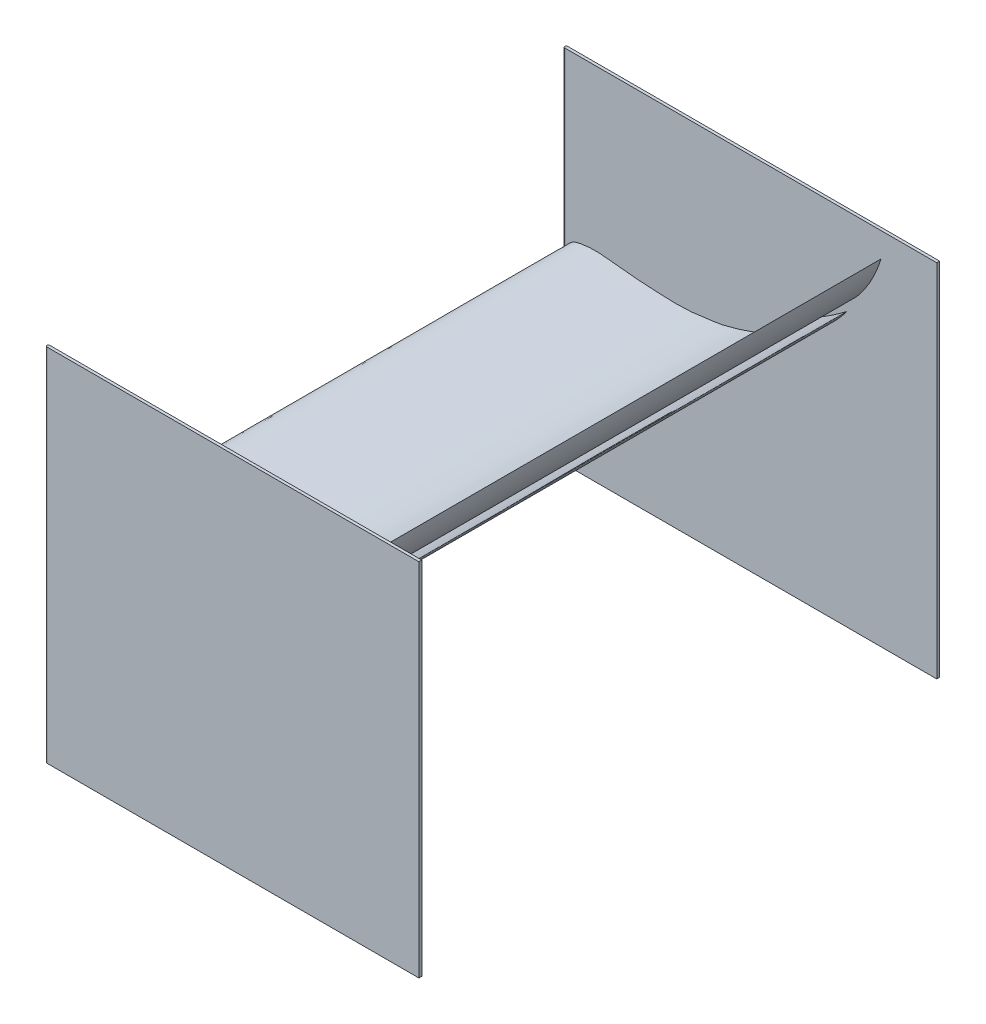
SolidWorks part; units mm, degrees
ref_plane "Front Plane" through (0, 0, 0) normal (0, 0, 1) x (1, 0, 0)
ref_plane "Top Plane" through (0, 0, 0) normal (0, 1, 0) x (1, 0, 0)
ref_plane "Right Plane" through (0, 0, 0) normal (1, 0, 0) x (0, 0, -1)
sketch "Sketch1" plane through (0, 0, 0) normal (0, 0, 1) x (1, 0, 0)
  line L0 (46.9575, 64.3181) -> (1074.8558, 208.7798) construction
sketch "Sketch2" plane through (0, 0, 0) normal (0, 0, 1) x (1, 0, 0)
  line L0 (0, 0) -> (400, 0) construction
  line L1 (0, 0) -> (399.6225, 66.8739) construction
  line L2 (0, 66.8739) -> (0, -66.8739) construction
  line L3 (10.0115, 66.8739) -> (10.0115, -116.1581) construction
  line L4 (20.0229, 66.8739) -> (20.0229, -116.1581) construction
  line L5 (30.0344, 66.8739) -> (30.0344, -116.1581) construction
  line L6 (40.0459, 66.8739) -> (40.0459, -116.1581) construction
  line L7 (50.0573, 66.8739) -> (50.0573, -116.1581) construction
  line L8 (60.0688, 66.8739) -> (60.0688, -116.1581) construction
  line L9 (70.0803, 66.8739) -> (70.0803, -116.1581) construction
  line L10 (80.0918, 66.8739) -> (80.0918, -116.1581) construction
  line L11 (90.1032, 66.8739) -> (90.1032, -116.1581) construction
  line L12 (100.1147, 66.8739) -> (100.1147, -116.1581) construction
  line L13 (110.1262, 66.8739) -> (110.1262, -116.1581) construction
  line L14 (120.1376, 66.8739) -> (120.1376, -116.1581) construction
  line L15 (130.1491, 66.8739) -> (130.1491, -116.1581) construction
  line L16 (140.1606, 66.8739) -> (140.1606, -116.1581) construction
  line L17 (150.172, 66.8739) -> (150.172, -116.1581) construction
  line L18 (160.1835, 66.8739) -> (160.1835, -116.1581) construction
  line L19 (170.195, 66.8739) -> (170.195, -116.1581) construction
  line L20 (180.2064, 66.8739) -> (180.2064, -116.1581) construction
  line L21 (190.2179, 66.8739) -> (190.2179, -116.1581) construction
  line L22 (200.2294, 66.8739) -> (200.2294, -116.1581) construction
  line L23 (210.2408, 66.8739) -> (210.2408, -116.1581) construction
  line L24 (220.2523, 66.8739) -> (220.2523, -116.1581) construction
  line L25 (230.2638, 66.8739) -> (230.2638, -116.1581) construction
  line L26 (240.2753, 66.8739) -> (240.2753, -116.1581) construction
  line L27 (250.2867, 66.8739) -> (250.2867, -116.1581) construction
  line L28 (260.2982, 66.8739) -> (260.2982, -116.1581) construction
  line L29 (270.3097, 66.8739) -> (270.3097, -116.1581) construction
  line L30 (280.3211, 66.8739) -> (280.3211, -116.1581) construction
  line L31 (290.3326, 66.8739) -> (290.3326, -116.1581) construction
  line L32 (300.3441, 66.8739) -> (300.3441, -116.1581) construction
  line L33 (310.3555, 66.8739) -> (310.3555, -116.1581) construction
  line L34 (320.367, 66.8739) -> (320.367, -116.1581) construction
  line L35 (330.3785, 66.8739) -> (330.3785, -116.1581) construction
  line L36 (340.3899, 66.8739) -> (340.3899, -116.1581) construction
  line L37 (350.4014, 66.8739) -> (350.4014, -116.1581) construction
  line L38 (360.4129, 66.8739) -> (360.4129, -116.1581) construction
  line L39 (370.4243, 66.8739) -> (370.4243, -116.1581) construction
  line L40 (380.4358, 66.8739) -> (380.4358, -116.1581) construction
  line L41 (390.4473, 66.8739) -> (390.4473, -116.1581) construction
  line L42 (400.4588, 66.8739) -> (400.4588, -116.1581) construction
  line L43 (836.1007, 66.8739) -> (-36.8556, 66.8739) construction
  line L44 (389.6225, 76.8739) -> (409.6225, 76.8739) construction
  line L45 (399.6225, 90.7703) -> (399.6225, 62.9774) construction
  line L46 (548.1427, 255.362) -> (478.7399, 156.2446) construction
  line L47 (488.7399, 146.2766) -> (482.6971, 142.1346) construction
  line L48 (389.6225, 76.8739) -> (488.7399, 146.2766) construction
  line L51 (488.7399, 194.8045) -> (488.7399, 123.7678) construction
  line L52 (478.7399, 201.6203) -> (478.7399, 116.9521) construction
  line L53 (478.7399, 156.2446) -> (614.5057, 156.2446) construction
  line L54 (389.6225, 83.3039) -> (389.6225, -27.4023) construction
  line L55 (478.7399, 146.2446) -> (614.5057, 146.2446) construction
  spline S0 degree 3 poles (8.4176, 12.2629) (-5.1, -0.6947) (8.0175, -15.4806) (19.5512, -21.724) (30.0167, -25.3022) (39.86, -28.8642) (50.0404, -30.6629) (60.0706, -32.2577) (70.0139, -34.2177) (80.101, -34.56) (90.0931, -35.3652) (100.112, -35.9529) (110.1282, -35.5072) (120.1532, -35.21) (130.1503, -34.2298) (140.19, -33.4102) (150.1782, -31.9134) (160.1704, -30.3713) (170.2408, -29.1636) (180.2083, -27.151) (190.2638, -25.3061) (200.2392, -22.8725) (210.2446, -20.4291) (220.2329, -17.8951) (230.3811, -15.7054) (240.3519, -12.3911) (253.5512, -7.3696) (266.9476, -2.8065) (280.4369, 1.6366) (290.3614, 5.8195) (300.4407, 10.0322) (310.3048, 14.8841) (323.8214, 20.8842) (337.3023, 27.2498) (350.2747, 34.8502) (364.0374, 41.2007) (378.0734, 50.4319) (389.2687, 56.9917) (404.9331, 70.6704) (388.8931, 60.8973) (380.9617, 56.8333) (370.3166, 52.1732) (360.4136, 47.7491) (350.4697, 43.0754) (340.4967, 38.8332) (330.4052, 35.261) (320.3498, 31.8494) (310.3583, 28.3259) (300.4869, 24.6622) (290.3218, 22.3006) (280.2904, 19.7619) (270.4267, 16.765) (260.336, 15.0613) (250.2769, 13.9588) (240.2662, 12.5783) (230.2787, 11.0679) (220.2867, 9.6964) (210.2433, 9.2404) (200.2287, 9.0345) (190.217, 8.2792) (180.2125, 9.1624) (170.1842, 8.7285) (160.1865, 9.5822) (150.1678, 9.9892) (140.1635, 10.7007) (130.146, 11.2145) (120.1214, 11.8409) (110.1328, 12.9697) (100.1148, 13.8501) (90.0938, 14.7159) (80.0796, 15.8427) (56.9177, 18.8475) (32.3828, 18.9634) (8.4176, 12.2629) (-5.1, -0.6947) (8.0175, -15.4806) knots -0.089629 -0.030705 -0.018228 0 0.022024 0.035622 0.048197 0.060585 0.072602 0.084545 0.096479 0.108284 0.12009 0.131879 0.143661 0.155449 0.167269 0.1791 0.190991 0.202897 0.214788 0.226766 0.238768 0.250864 0.262992 0.27512 0.287235 0.299601 0.31215 0.337082 0.349542 0.362249 0.375072 0.388091 0.40103 0.427261 0.440709 0.453892 0.481344 0.495528 0.510184 0.522428 0.535733 0.548643 0.561554 0.574511 0.587287 0.599816 0.612271 0.624763 0.637218 0.649381 0.661544 0.67375 0.685718 0.697586 0.709472 0.721375 0.733243 0.74504 0.756824 0.768611 0.780398 0.792175 0.803972 0.815766 0.827567 0.839363 0.851169 0.863006 0.874833 0.88666 0.89851 0.910371 0.969295 0.981772 1 1.022024 1.035622 1.048197 only from (0, 0) to (0, 0)
  spline S1 degree 3 poles (488.4807, 145.9571) (488.8121, 146.3498) (488.4243, 146.015) (488.0622, 145.7851) (487.2625, 145.1263) (486.2197, 144.3713) (484.8735, 143.3367) (483.2507, 142.1161) (481.3449, 140.7026) (479.1839, 139.1083) (476.7613, 137.3643) (474.1237, 135.4494) (471.2368, 133.4393) (468.1657, 131.2913) (464.8962, 129.0676) (461.4575, 126.7695) (457.874, 124.4106) (454.1513, 122.027) (450.3296, 119.6083) (446.4184, 117.1921) (442.4423, 114.7926) (438.4319, 112.4153) (434.4211, 110.0589) (430.4193, 107.7484) (426.4691, 105.4752) (422.5724, 103.27) (418.7829, 101.1054) (415.1038, 99.0189) (411.5811, 96.98) (408.2231, 95.0247) (405.0701, 93.1172) (402.1178, 91.3128) (399.4157, 89.5543) (396.9653, 87.8935) (394.7924, 86.3186) (392.9158, 84.83) (391.3498, 83.4309) (390.0835, 82.1509) (389.1526, 80.9646) (388.5665, 79.872) (388.3105, 78.8689) (388.4525, 77.9475) (389.0134, 77.2045) (389.9156, 76.685) (391.1282, 76.3842) (392.6501, 76.2546) (394.4851, 76.3138) (396.6232, 76.5794) (399.0459, 77.0357) (401.7358, 77.7205) (404.6757, 78.5968) (407.8392, 79.7049) (411.2008, 81.0269) (414.7209, 82.591) (418.3956, 84.3418) (422.1799, 86.3091) (426.0457, 88.48) (429.9704, 90.8288) (433.915, 93.3645) (437.8712, 96.0402) (441.7934, 98.8661) (445.6685, 101.7972) (449.4657, 104.8272) (453.1679, 107.924) (456.7615, 111.054) (460.2029, 114.2195) (463.5191, 117.343) (466.6501, 120.455) (469.6136, 123.4898) (472.3702, 126.4509) (474.954, 129.2656) (477.2978, 131.9605) (479.4562, 134.4635) (481.3811, 136.7846) (483.0779, 138.8974) (484.5577, 140.7696) (485.8099, 142.3825) (486.8479, 143.7389) (487.6258, 144.7686) (488.2511, 145.5957) (488.4807, 145.9571) (488.8121, 146.3498) (488.4243, 146.015) knots -0.00692 -0.003098 -0.00077 0 0.000781 0.003074 0.006931 0.012248 0.01903 0.027226 0.036785 0.04761 0.059602 0.072764 0.086897 0.102004 0.117939 0.134556 0.151858 0.169651 0.187838 0.206374 0.225065 0.243814 0.262569 0.281137 0.299514 0.317506 0.335105 0.352118 0.368488 0.384167 0.398955 0.412906 0.425872 0.437811 0.448585 0.458213 0.466669 0.473884 0.479894 0.484779 0.488743 0.492167 0.495628 0.499576 0.504487 0.510576 0.517943 0.526574 0.536524 0.54764 0.560015 0.573491 0.588031 0.603544 0.619912 0.637089 0.654944 0.673346 0.692212 0.711461 0.73091 0.750475 0.770022 0.789461 0.808651 0.827458 0.84582 0.863559 0.880666 0.896945 0.912322 0.926718 0.939993 0.952161 0.96306 0.972662 0.980906 0.987733 0.99308 0.996902 0.99923 1 1.000781 1.003074 1.006931 only from (488.7399, 146.2766) to (488.7399, 146.2766)
  spline S2 degree 3 poles (548.0012, 254.9703) (548.1874, 255.456) (547.9279, 255.0069) (547.6584, 254.6667) (547.113, 253.7707) (546.3674, 252.702) (545.4246, 251.265) (544.2794, 249.5582) (542.9279, 247.5728) (541.3924, 245.3297) (539.6567, 242.8564) (537.7725, 240.1482) (535.6814, 237.266) (533.4602, 234.1907) (531.0746, 230.977) (528.5519, 227.6359) (525.9111, 224.1885) (523.1453, 220.6711) (520.2967, 217.0873) (517.3615, 213.4761) (514.3589, 209.8593) (511.316, 206.2523) (508.2658, 202.665) (505.209, 199.1247) (502.189, 195.6372) (499.1976, 192.2326) (496.2952, 188.9024) (493.4722, 185.6835) (490.783, 182.5623) (488.2235, 179.5757) (485.844, 176.7031) (483.6219, 173.9957) (481.6239, 171.4156) (479.834, 169.0126) (478.2807, 166.784) (476.9821, 164.7365) (475.9505, 162.878) (475.1658, 161.233) (474.6707, 159.7892) (474.4739, 158.5497) (474.5629, 157.5056) (475.0053, 156.672) (475.7887, 156.1483) (476.824, 155.9518) (478.0833, 156.0678) (479.5813, 156.4503) (481.3159, 157.1174) (483.2715, 158.0828) (485.4358, 159.3251) (487.7794, 160.8747) (490.2983, 162.6906) (492.9538, 164.8026) (495.7276, 167.1848) (498.5723, 169.8513) (501.5026, 172.7478) (504.4658, 175.8877) (507.4391, 179.2493) (510.4095, 182.8005) (513.3367, 186.5371) (516.2285, 190.4114) (519.0377, 194.4179) (521.767, 198.5093) (524.3889, 202.6695) (526.8977, 206.8618) (529.2916, 211.0497) (531.5283, 215.2209) (533.6592, 219.3103) (535.617, 223.3271) (537.4402, 227.2144) (539.0902, 230.9623) (540.6237, 234.5128) (541.9677, 237.8689) (543.1982, 240.9799) (544.2661, 243.8393) (545.1852, 246.4237) (545.977, 248.7058) (546.6373, 250.6644) (547.1783, 252.3065) (547.5794, 253.5497) (547.9019, 254.5484) (548.0012, 254.9703) (548.1874, 255.456) (547.9279, 255.0069) knots -0.00692 -0.003098 -0.00077 0 0.000781 0.003074 0.006931 0.012248 0.01903 0.027226 0.036785 0.04761 0.059602 0.072764 0.086897 0.102004 0.117939 0.134556 0.151858 0.169651 0.187838 0.206374 0.225065 0.243814 0.262569 0.281137 0.299514 0.317506 0.335105 0.352118 0.368488 0.384167 0.398955 0.412906 0.425872 0.437811 0.448585 0.458213 0.466669 0.473884 0.479894 0.484779 0.488743 0.492167 0.495628 0.499576 0.504487 0.510576 0.517943 0.526574 0.536524 0.54764 0.560015 0.573491 0.588031 0.603544 0.619912 0.637089 0.654944 0.673346 0.692212 0.711461 0.73091 0.750475 0.770022 0.789461 0.808651 0.827458 0.84582 0.863559 0.880666 0.896945 0.912322 0.926718 0.939993 0.952161 0.96306 0.972662 0.980906 0.987733 0.99308 0.996902 0.99923 1 1.000781 1.003074 1.006931 only from (548.1427, 255.362) to (548.1427, 255.362)
  point P7 (0, 0)
  point P94 (399.6225, 76.8739)
  point P100 (399.6225, 76.8739)
  point P108 (399.6225, 66.8739)
  point P112 (389.6225, 76.8739)
  point P126 (488.7399, 146.2766)
  point P130 (488.7399, 156.2766)
  point P136 (488.7399, 159.2862)
  point P142 (478.7399, 159.2862)
  dimension "D1" = 9.5
  dimension "D3" = 405.1793
  dimension "D4" = 400
  dimension "D5" = 121
  dimension "D6" = 10
  dimension "D7" = 35
  dimension "D8" = 10
  dimension "D9" = 55
  dimension "D10" = 10
  dimension "D11" = 121
  dimension "D12" = 10
  dimension "D13" = 79.3707
  dimension "D2" = 41
extrude "Boss-Extrude1" add sketch "Sketch2" along normal blind 900
ref_plane "Plane1" through (0, 0, 900) normal (0, 0, 1) x (1, 0, 0)
sketch "Sketch3" plane through (0, 0, 900) normal (0, 0, 1) x (1, 0, 0)
  line L0 (535.5966, 298.3743) -> (535.5966, -331.6257) construction
  line L1 (-4.4034, 298.3743) -> (645.5966, 298.3743)
  line L2 (-4.4034, 298.3743) -> (-4.4034, -331.6257)
  line L3 (-4.4034, -331.6257) -> (645.5966, -331.6257)
  line L4 (645.5966, 298.3743) -> (645.5966, -331.6257)
  dimension "D1" = 110
  dimension "D2" = 650
  dimension "D3" = 630
extrude "Boss-Extrude2" add sketch "Sketch3" along normal blind 5
sketch "Sketch5" plane through (0, 0, 0) normal (0, 0, 1) x (1, 0, 0)
  line L0 (535.5966, 298.3743) -> (535.5966, -331.6257) construction
  line L1 (-4.4034, 298.3743) -> (645.5966, 298.3743)
  line L2 (-4.4034, 298.3743) -> (-4.4034, -331.6257)
  line L3 (-4.4034, -331.6257) -> (645.5966, -331.6257)
  line L4 (645.5966, 298.3743) -> (645.5966, -331.6257)
  dimension "D1" = 110
  dimension "D2" = 650
  dimension "D3" = 630
extrude "Boss-Extrude3" add sketch "Sketch5" against normal blind 5 contours L2 L3 L4 L1
sketch "Sketch8" plane through (0, 298.3743, 0) normal (0, 1, 0) x (1, 0, 0)
  line L0 (-4.4034, 5) -> (-4.4034, 0) construction
  line L1 (-4.4034, -905) -> (-4.4034, -900) construction
  line L2 (-4.4034, -900) -> (-4.4034, -905)
  line L3 (-4.4034, 5) -> (-4.4034, 0)
  arc A0 (-4.4034, 5) -> (-4.4034, 0) centre (-4.4034, 2.5) ccw
  arc A1 (-4.4034, -900) -> (-4.4034, -905) centre (-4.4034, -902.5) ccw
extrude "Boss-Extrude4" add sketch "Sketch8" against normal blind 630
ref_plane "Plane2" through (0, 0, 450) normal (0, 0, 1) x (1, 0, 0)
